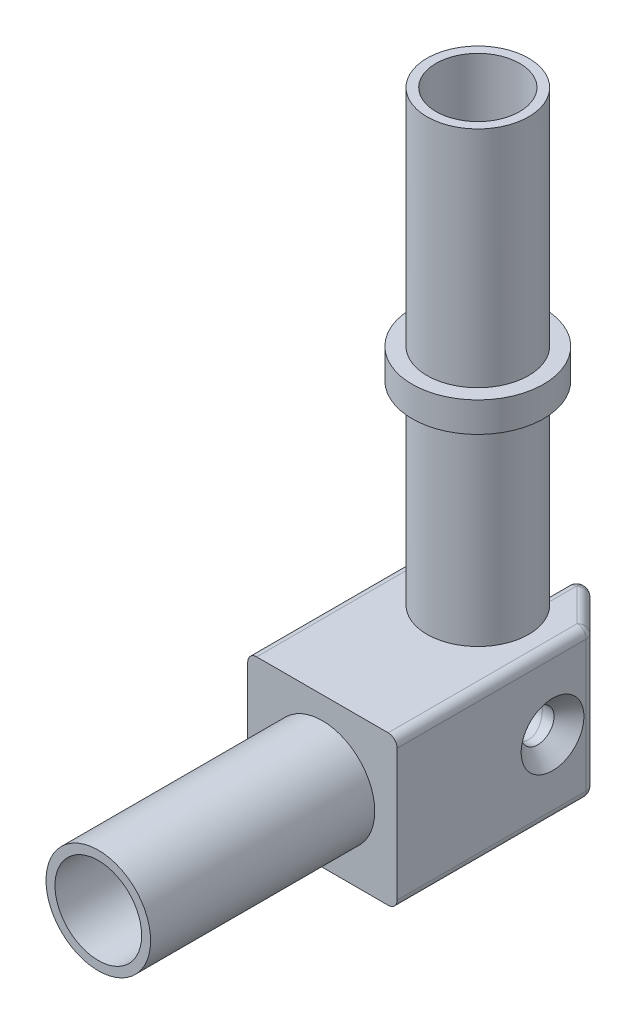
SolidWorks part; units mm, degrees
ref_plane "Front Plane" through (0, 0, 0) normal (0, 0, 1) x (1, 0, 0)
ref_plane "Top Plane" through (0, 0, 0) normal (0, 1, 0) x (1, 0, 0)
ref_plane "Right Plane" through (0, 0, 0) normal (1, 0, 0) x (0, 0, -1)
sketch "Sketch1" plane through (0, 0, 0) normal (0, 0, 1) x (1, 0, 0)
  line L1 (-37.5, -37.5) -> (37.5, -37.5)
  line L2 (-37.5, -37.5) -> (-37.5, 37.5)
  line L3 (-37.5, 37.5) -> (37.5, 37.5)
  line L4 (37.5, -37.5) -> (37.5, 37.5)
  line L5 (-37.5, -37.5) -> (37.5, 37.5) construction
  line L6 (-37.5, 37.5) -> (37.5, -37.5) construction
  point P0 (0, 0)
  dimension "D1" = 75
  dimension "D2" = 75
extrude "Boss-Extrude1" add sketch "Sketch1" along normal blind 8
fillet "Fillet1" radius 10 4 edges at (37.5, -37.5, 4) (-37.5, -37.5, 4) (37.5, 37.5, 4) (-37.5, 37.5, 4)
sketch "Sketch2" plane through (0, 0, 0) normal (0, 1, 0) x (1, 0, 0)
  line L0 (-27.5, -8) -> (-27.5, -30)
  line L1 (27.5, -30) -> (27.5, -8)
  line L2 (27.5, -8) -> (-27.5, -8)
  circle A0 centre (0, -30) radius 17.5
  arc A1 (-27.5, -30) -> (27.5, -30) centre (0, -30) ccw
  dimension "D1" = 35
  dimension "D2" = 30
extrude "Boss-Extrude2" add sketch "Sketch2" along normal mid plane 75
sketch "Sketch3" plane through (0, 37.5, 0) normal (0, 1, 0) x (1, 0, 0)
  circle A2 centre (0, -30) radius 17
  circle A3 centre (0, -30) radius 17
  dimension "D1" = 0.5
extrude "Boss-Extrude3" add sketch "Sketch3" against normal blind 200 separate body
sketch "Sketch4" plane through (0, -37.5, 0) normal (0, -1, 0) x (1, 0, 0)
  circle A1 centre (0, 30) radius 17
  circle A2 centre (0, 30) radius 17
  circle A4 centre (0, 30) radius 22
  circle A5 centre (0, 30) radius 22
  dimension "D1" = 0
  dimension "D2" = 5
extrude "Boss-Extrude4" add sketch "Sketch4" along normal blind 10
sketch "Sketch5" plane through (0, -162.5, 0) normal (0, -1, 0) x (1, 0, 0)
  line L0 (-8, 15) -> (-8, 5)
  line L1 (-8, 5) -> (-12.5, 5)
  line L2 (-12.5, 5) -> (-25, 17.5)
  line L3 (-25, 17.5) -> (-25, 82)
  line L4 (0, 0) -> (0, 57.5) construction
  line L5 (-25, 82) -> (0, 82)
  line L6 (0, 82) -> (0, 47)
  arc A0 (27.5, 30) -> (-27.5, 30) centre (0, 30) ccw construction
  circle A1 centre (0, 30) radius 17
  arc A2 (0, 47) -> (-8, 15) centre (0, 30) ccw
  dimension "D2" = 8
  dimension "D3" = 10
  dimension "D4" = 25
  dimension "D5" = 45
  dimension "D6" = 12.5
  dimension "D7" = 35
  dimension "D1" = 0
extrude "Boss-Extrude5" add sketch "Sketch5" against normal blind 50 separate body
mirror "Mirror1" about plane through (0, -112.5, 82) normal (1, 0, 0) of bodies 105
sketch "Sketch6" plane through (0, 0, 82) normal (0, 0, 1) x (1, 0, 0)
  line L0 (-25, -112.5) -> (25, -162.5) construction
  circle A0 centre (0, -137.5) radius 17.5
  dimension "D1" = 35
extrude "Cut-Extrude1" cut sketch "Sketch6" against normal blind 25
sketch "Sketch7" plane through (0, 0, 57) normal (0, 0, 1) x (1, 0, 0)
  circle A1 centre (0, -137.5) radius 17.5
  circle A2 centre (0, -137.5) radius 17.5
  dimension "D1" = 0
extrude "Boss-Extrude6" add sketch "Sketch7" along normal blind 100 separate body
sketch "Sketch8" plane through (25, 0, 0) normal (1, 0, 0) x (0, 0, -1)
  line L0 (-30, -47.5) -> (-30, -112.5) construction
  line L1 (-47, -47.5) -> (-13, -47.5) construction
  line L2 (-82, -112.5) -> (-17.5, -112.5) construction
  line L3 (-30, -112.5) -> (-30, -162.5) construction
  line L4 (-82, -162.5) -> (-17.5, -162.5) construction
  circle A0 centre (-30, -137.5) radius 5.5
  dimension "D1" = 11
extrude "Cut-Extrude2" cut sketch "Sketch8" against normal through all both and the other way through all
sketch "Sketch10" plane through (0, -162.5, 0) normal (0, -1, 0) x (1, 0, 0)
  circle A4 centre (0, 30) radius 14
  circle A5 centre (0, 30) radius 14
  dimension "D1" = 3
extrude "Cut-Extrude3" cut sketch "Sketch10" against normal through all both
chamfer "Chamfer1" distance 5 angle 45 1 edges at (25, -137.5, 24.5)
sketch "Sketch11" plane through (-25, 0, 0) normal (-1, 0, 0) x (0, 0, 1)
  line L1 (39, -142.6962) -> (39, -132.3038)
  line L2 (39, -132.3038) -> (30, -127.1077)
  line L3 (30, -127.1077) -> (21, -132.3038)
  line L4 (21, -132.3038) -> (21, -142.6962)
  line L5 (21, -142.6962) -> (30, -147.8923)
  line L6 (30, -147.8923) -> (39, -142.6962)
  circle A0 centre (30, -137.5) radius 9 construction
  dimension "D1" = 18
extrude "Cut-Extrude4" cut sketch "Sketch11" against normal blind 12
fillet "Fillet3" radius 3 6 edges at (-12.5, -137.5, 5) (12.5, -137.5, 5) (8, -137.5, 5) (-8, -137.5, 5) (25, -137.5, 17.5) (-25, -137.5, 17.5)
fillet "Fillet2" radius 3 28 edges at (12.4054, -162.5, 5.2284) (-12.4054, -162.5, 5.2284) (-11.1287, -112.5, 5) (-8, -112.5, 11.5) (18.75, -112.5, 11.25) (11.1287, -112.5, 5) (8, -112.5, 11.5) (-24.7716, -112.5, 17.5946) (24.7716, -112.5, 17.5946) (-8.8787, -112.5, 5.8787) (8.8787, -112.5, 5.8787) (12.4054, -112.5, 5.2284) (-12.4054, -112.5, 5.2284) (-25, -112.5, 50.3713) (25, -162.5, 50.3713) (25, -112.5, 50.3713) (-25, -162.5, 50.3713) (-18.75, -162.5, 11.25) (-18.75, -112.5, 11.25) (8, -162.5, 11.5) (11.1287, -162.5, 5) (18.75, -162.5, 11.25) (-11.1287, -162.5, 5) (-8, -162.5, 11.5) (-24.7716, -162.5, 17.5946) (24.7716, -162.5, 17.5946) (-8.8787, -162.5, 5.8787) (8.8787, -162.5, 5.8787)
delete or keep bodies "Body-Delete/Keep 1" type delete bodies bodies 102
sketch "Sketch12" plane through (0, 0, 157) normal (0, 0, 1) x (1, 0, 0)
  circle A3 centre (0, -137.5) radius 14.5
  circle A4 centre (0, -137.5) radius 14.5
  dimension "D1" = 3
extrude "Cut-Extrude5" cut sketch "Sketch12" against normal through all
